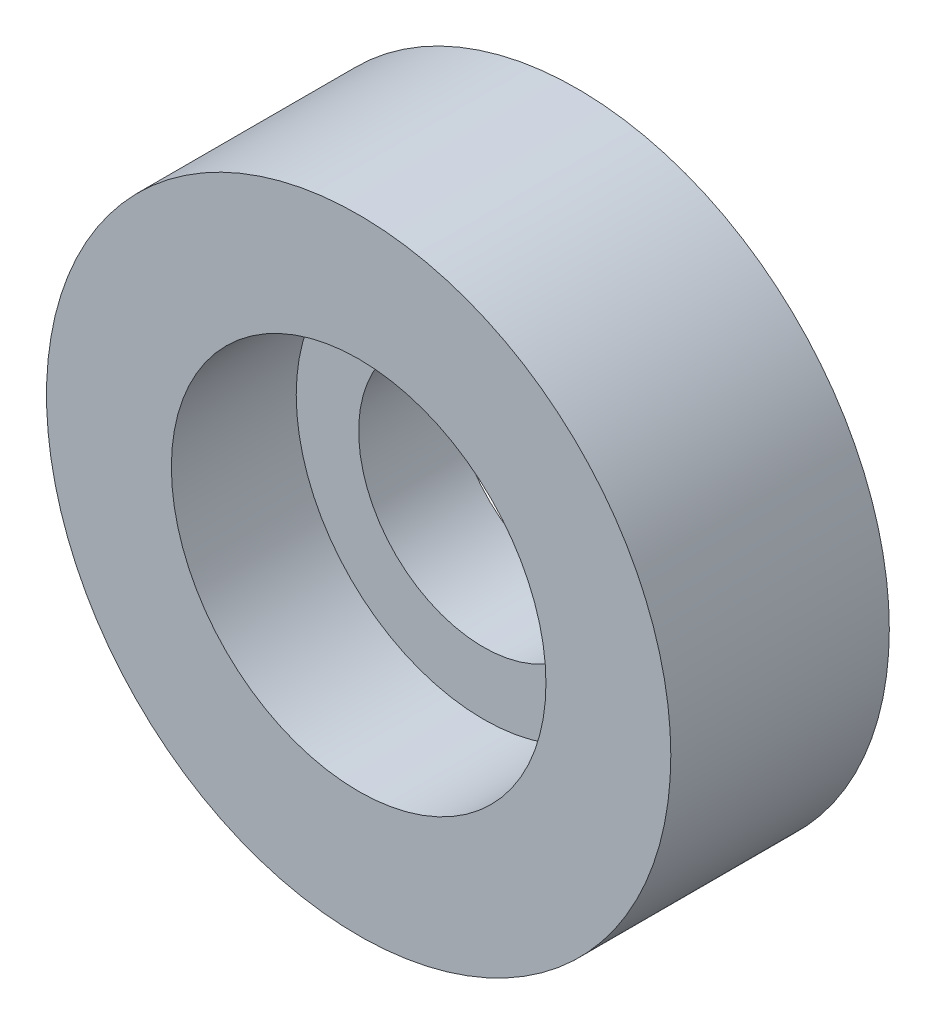
SolidWorks part; units mm, degrees
ref_plane "Front Plane" through (0, 0, 0) normal (0, 0, 1) x (1, 0, 0)
ref_plane "Top Plane" through (0, 0, 0) normal (0, 1, 0) x (1, 0, 0)
ref_plane "Right Plane" through (0, 0, 0) normal (1, 0, 0) x (0, 0, -1)
sketch "Sketch1" plane through (0, 0, 0) normal (0, 0, 1) x (1, 0, 0)
  circle A0 centre (0, 0) radius 5
  circle A1 centre (0, 0) radius 2
  dimension "D1" = 4
  dimension "D2" = 10
extrude "Boss-Extrude1" add sketch "Sketch1" along normal blind 1.5
sketch "Sketch2" plane through (0, 0, 1.5) normal (0, 0, 1) x (1, 0, 0)
  circle A0 centre (0, 0) radius 5
  circle A1 centre (0, 0) radius 3
  dimension "D1" = 6
extrude "Boss-Extrude2" add sketch "Sketch2" along normal blind 2
